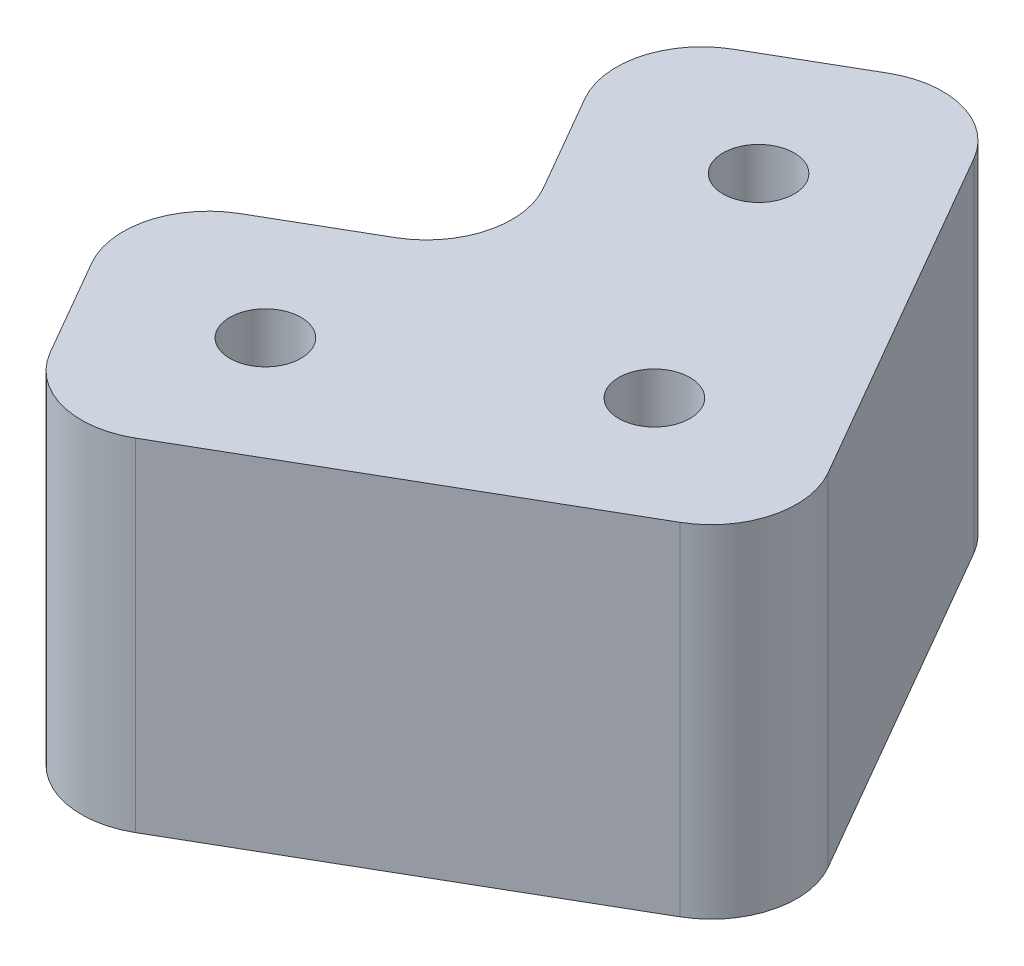
SolidWorks part; units mm, degrees
ref_plane "前视基准面" through (0, 0, 0) normal (0, 0, 1) x (1, 0, 0)
ref_plane "上视基准面" through (0, 0, 0) normal (0, 1, 0) x (1, 0, 0)
ref_plane "右视基准面" through (0, 0, 0) normal (1, 0, 0) x (0, 0, -1)
other "Configuration Table"
sketch "草图1" plane through (0, 0, 0) normal (0, 1, 0) x (1, 0, 0)
  line L0 (0, 0) -> (65, 0)
  line L1 (0, 0) -> (-65, 0)
  line L2 (0, 0) -> (0, -65) construction
  circle A0 centre (0, 0) radius 55
  circle A1 centre (0, 0) radius 65
  dimension "D2" = 10
  dimension "D3" = 65
  dimension "D1" = 90
extrude "凸台-拉伸1" [suppressed] add sketch "草图1" along normal blind 2 contours L2 A0 L1 A1 | A0 L2 A1 L0
sketch "草图2" [suppressed] plane through (0, 0, 0) normal (0, 1, 0) x (1, 0, 0)
  line L5 (0, 0) -> (0, -65) construction
  line L10 (0, 0) -> (-56.2917, -32.5) construction
  line L11 (2.5, -4.3301) -> (-53.7917, -36.8301) construction
  line L12 (-2.5, 4.3301) -> (-58.7917, -28.1699) construction
  line L13 (-58.6249, -28.0736) -> (-49.9342, -23.056)
  line L14 (-58.6249, -28.0736) -> (-63.6249, -19.4133)
  line L15 (-63.6249, -19.4133) -> (-54.9342, -14.3957)
  line L16 (-54.9342, -14.3957) -> (-49.9342, -23.056)
  line L17 (58.6249, -28.0736) -> (63.6249, -19.4133)
  line L18 (58.6249, -28.0736) -> (49.9342, -23.056)
  line L19 (63.6249, -19.4133) -> (54.9342, -14.3957)
  line L20 (54.9342, -14.3957) -> (49.9342, -23.056)
  arc A0 (-65, 0) -> (65, 0) centre (0, 0) ccw construction
  arc A1 (2.5, -4.3301) -> (-2.5, 4.3301) centre (0, 0) ccw construction
  arc A3 (-58.7917, -28.1699) -> (-53.7917, -36.8301) centre (-56.2917, -32.5) ccw construction
  arc A5 (-55, 0) -> (55, 0) centre (0, 0) ccw construction
  point P3 (-28.1458, -16.25)
  dimension "D1" = 5
  dimension "D2" = 65
  dimension "D3" = 60
  dimension "D4" = 10
extrude "凸台-拉伸2" [suppressed] add sketch "草图2" along normal blind 12
sketch "草图3" plane through (0, 0, 0) normal (0, 1, 0) x (1, 0, 0)
  line L0 (0, 0) -> (-56.2917, -32.5) construction
  line L1 (2.5, -4.3301) -> (-53.7917, -36.8301) construction
  line L2 (-2.5, 4.3301) -> (-58.7917, -28.1699) construction
  line L3 (0, 0) -> (0, -57.3049) construction
  line L4 (-51.9615, -30) -> (-56.9615, -21.3397) construction
  line L5 (-56.9615, -21.3397) -> (-61.9615, -12.6795) construction
  line L6 (-56.9615, -21.3397) -> (-65.6218, -26.3397) construction
  line L7 (-68.7917, -10.8494) -> (-60.1314, -5.8494)
  line L8 (-60.1314, -5.8494) -> (-50.1314, -23.1699)
  line L9 (-50.1314, -23.1699) -> (-67.4519, -33.1699)
  line L10 (-67.4519, -33.1699) -> (-72.4519, -24.5096)
  line L11 (-72.4519, -24.5096) -> (-63.7917, -19.5096)
  line L12 (-63.7917, -19.5096) -> (-68.7917, -10.8494)
  arc A0 (2.5, -4.3301) -> (-2.5, 4.3301) centre (0, 0) ccw construction
  arc A1 (-58.7917, -28.1699) -> (-53.7917, -36.8301) centre (-56.2917, -32.5) ccw construction
  circle A2 centre (-56.9615, -21.3397) radius 1.25
  circle A3 centre (-61.9615, -12.6795) radius 1.25
  circle A4 centre (-65.6218, -26.3397) radius 1.25
  point P3 (-28.1458, -16.25)
  dimension "D2" = 5
  dimension "D5" = 2.5
  dimension "D1" = 65
  dimension "D3" = 60
  dimension "D4" = 60
  dimension "D6" = 10
  dimension "D7" = 10
  dimension "D8" = 10
  dimension "D9" = 10
  dimension "D10" = 5
extrude "凸台-拉伸3" add sketch "草图3" along normal blind 12
fillet "圆角1" radius 3 6 edges at (-68.7917, 6, 10.8494) (-60.1314, 6, 5.8494) (-50.1314, 6, 23.1699) (-67.4519, 6, 33.1699) (-63.7917, 6, 19.5096) (-72.4519, 6, 24.5096)
hole_wizard "M3 螺纹孔1" positions "3D草图1" profile "草图4" tap size "M3" standard "GB" end condition up to next
sketch3d "3D草图1"
  line L0 (-61.9615, 12, 12.6795) -> (-61.9615, 0, 12.6795) construction
  line L1 (-56.9615, 12, 21.3397) -> (-56.9615, 0, 21.3397) construction
  line L2 (-65.6218, 12, 26.3397) -> (-65.6218, 0, 26.3397) construction
  point P0 (-61.9615, 12, 12.6795)
  point P4 (-56.9615, 12, 21.3397)
  point P8 (-65.6218, 12, 26.3397)
sketch "草图4" plane through (-61.9615, 12, 12.6795) normal (1, 0, 0) x (0, 0, 1)
  line L0 (0, 0) -> (0, 12)
  line L1 (0, 12) -> (1.25, 12)
  line L2 (1.25, 12) -> (1.25, 0)
  line L5 (1.25, 0) -> (0, 0)
  line L11 (0, -6.35) -> (0, 107.95) construction
  dimension "通孔螺纹孔钻头直径" = 2.5
  dimension "通孔螺纹孔钻头深度" = 12
cosmetic thread "孔螺纹线1" parameters "D2"=3
cosmetic thread "孔螺纹线2" parameters "D2"=3
cosmetic thread "孔螺纹线3" parameters "D2"=3
